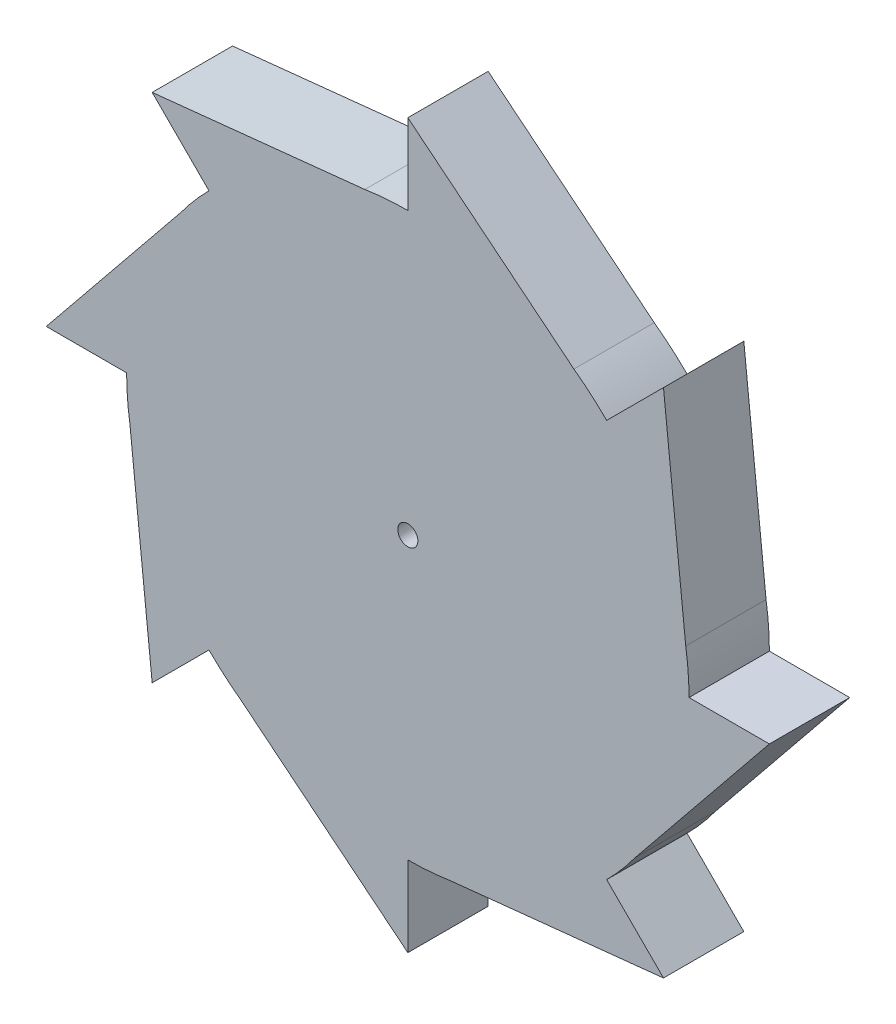
SolidWorks part; units mm, degrees
ref_plane "Front Plane" through (0, 0, 0) normal (0, 0, 1) x (1, 0, 0)
ref_plane "Top Plane" through (0, 0, 0) normal (0, 1, 0) x (1, 0, 0)
ref_plane "Right Plane" through (0, 0, 0) normal (1, 0, 0) x (0, 0, -1)
sketch "Sketch1" plane through (0, 0, 0) normal (0, 0, 1) x (1, 0, 0)
  line L0 (0, 22.225) -> (0, 28.575)
  line L1 (0, 0) -> (17.6612, 24.1301) construction
  line L2 (0, 28.575) -> (13.1265, 17.9345)
  line L3 (15.7154, 15.7154) -> (20.2056, 20.2056)
  line L4 (20.2056, 20.2056) -> (21.9634, 3.3998)
  line L5 (22.225, 0) -> (28.575, 0)
  line L6 (28.575, 0) -> (17.9345, -13.1265)
  line L7 (15.7154, -15.7154) -> (20.2056, -20.2056)
  line L8 (20.2056, -20.2056) -> (3.3998, -21.9634)
  line L9 (0, -22.225) -> (0, -28.575)
  line L10 (0, -28.575) -> (-13.1265, -17.9345)
  line L11 (-15.7154, -15.7154) -> (-20.2056, -20.2056)
  line L12 (-20.2056, -20.2056) -> (-21.9634, -3.3998)
  line L13 (-22.225, 0) -> (-28.575, 0)
  line L14 (-28.575, 0) -> (-17.9345, 13.1265)
  line L15 (-15.7154, 15.7154) -> (-20.2056, 20.2056)
  line L16 (-20.2056, 20.2056) -> (-3.3998, 21.9634)
  arc A0 (0, 22.225) -> (-3.3998, 21.9634) centre (0, 0) ccw
  arc A1 (15.7154, 15.7154) -> (13.1265, 17.9345) centre (0, 0) ccw
  arc A2 (22.225, 0) -> (21.9634, 3.3998) centre (0, 0) ccw
  arc A3 (15.7154, -15.7154) -> (17.9345, -13.1265) centre (0, 0) ccw
  arc A4 (0, -22.225) -> (3.3998, -21.9634) centre (0, 0) ccw
  arc A5 (-15.7154, -15.7154) -> (-13.1265, -17.9345) centre (0, 0) ccw
  arc A6 (-22.225, 0) -> (-21.9634, -3.3998) centre (0, 0) ccw
  arc A7 (-15.7154, 15.7154) -> (-17.9345, 13.1265) centre (0, 0) ccw
  point P31 (0, 0)
  dimension "D1" = 44.45
  dimension "D2" = 6.35
  dimension "D3" = 8
extrude "Boss-Extrude1" add sketch "Sketch1" along normal blind 6.35
sketch "Sketch2" plane through (0, 0, 6.35) normal (0, 0, 1) x (1, 0, 0)
  circle A0 centre (0, 0) radius 0.7938
  dimension "D1" = 1.5875
extrude "Cut-Extrude1" cut sketch "Sketch2" against normal through all
